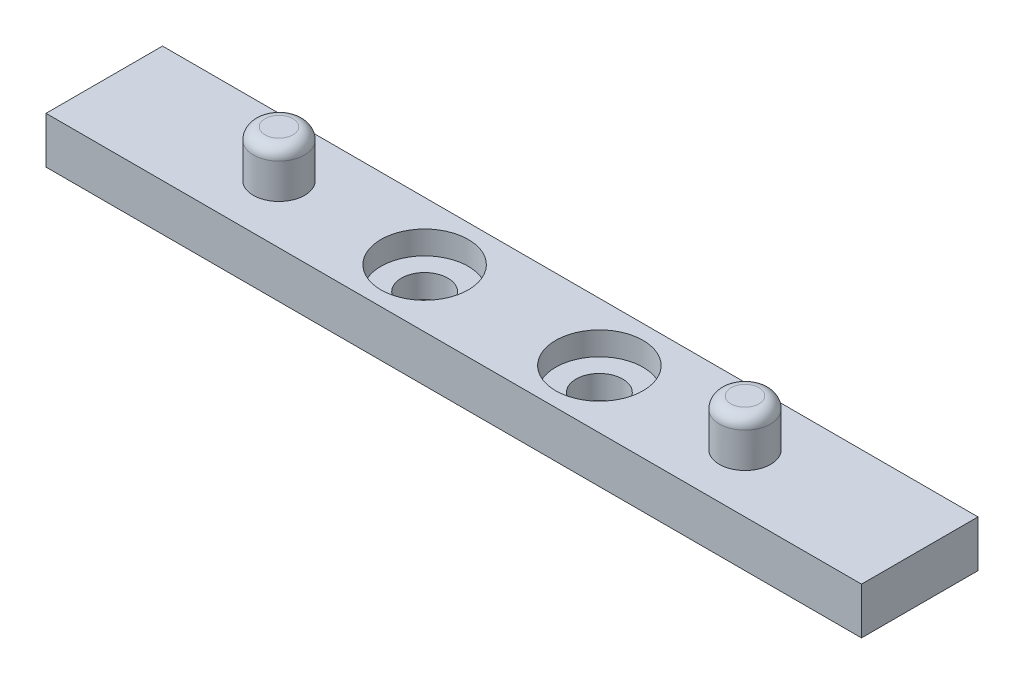
SolidWorks part; units mm, degrees
ref_plane "Front Plane" through (0, 0, 0) normal (0, 0, 1) x (1, 0, 0)
ref_plane "Top Plane" through (0, 0, 0) normal (0, 1, 0) x (1, 0, 0)
ref_plane "Right Plane" through (0, 0, 0) normal (1, 0, 0) x (0, 0, -1)
sketch "Sketch1" plane through (0, 0, 0) normal (0, 1, 0) x (1, 0, 0)
  line L0 (0, 6.35) -> (88.9, 6.35) construction
  line L1 (0, 0) -> (88.9, 0)
  line L2 (0, 0) -> (0, 12.7)
  line L3 (0, 12.7) -> (88.9, 12.7)
  line L4 (88.9, 0) -> (88.9, 12.7)
  line L5 (44.45, 12.7) -> (44.45, 0) construction
  circle A0 centre (34.925, 6.35) radius 2.54
  circle A1 centre (53.975, 6.35) radius 2.54
  dimension "D5" = 5.08
  dimension "D6" = 5.08
  dimension "D1" = 12.7
  dimension "D2" = 88.9
  dimension "D3" = 19.05
  dimension "D4" = 9.525
extrude "Boss-Extrude2" add sketch "Sketch1" along normal blind 5.08
sketch "Sketch2" plane through (0, 5.08, 0) normal (0, 1, 0) x (1, 0, 0)
  line L0 (0, 6.35) -> (88.9, 6.35) construction
  line L1 (0, 12.7) -> (0, 0) construction
  line L2 (88.9, 0) -> (88.9, 12.7) construction
  line L3 (44.45, 12.7) -> (44.45, 0) construction
  line L4 (88.9, 12.7) -> (0, 12.7) construction
  line L5 (0, 0) -> (88.9, 0) construction
  circle A0 centre (19.05, 6.35) radius 2.794
  circle A1 centre (69.85, 6.35) radius 2.794
  dimension "D1" = 5.588
  dimension "D2" = 5.588
  dimension "D3" = 50.8
  dimension "D4" = 25.4
extrude "Boss-Extrude3" add sketch "Sketch2" along normal blind 5.08
fillet "Fillet1" radius 1.27 2 edges at (69.85, 10.16, -3.556) (19.05, 10.16, -3.556)
sketch "Sketch3" plane through (0, 5.08, 0) normal (0, 1, 0) x (1, 0, 0)
  circle A0 centre (34.925, 6.35) radius 4.7625
  circle A1 centre (53.975, 6.35) radius 4.7625
  dimension "D1" = 9.525
  dimension "D2" = 9.525
extrude "Cut-Extrude1" cut sketch "Sketch3" against normal blind 2.54
